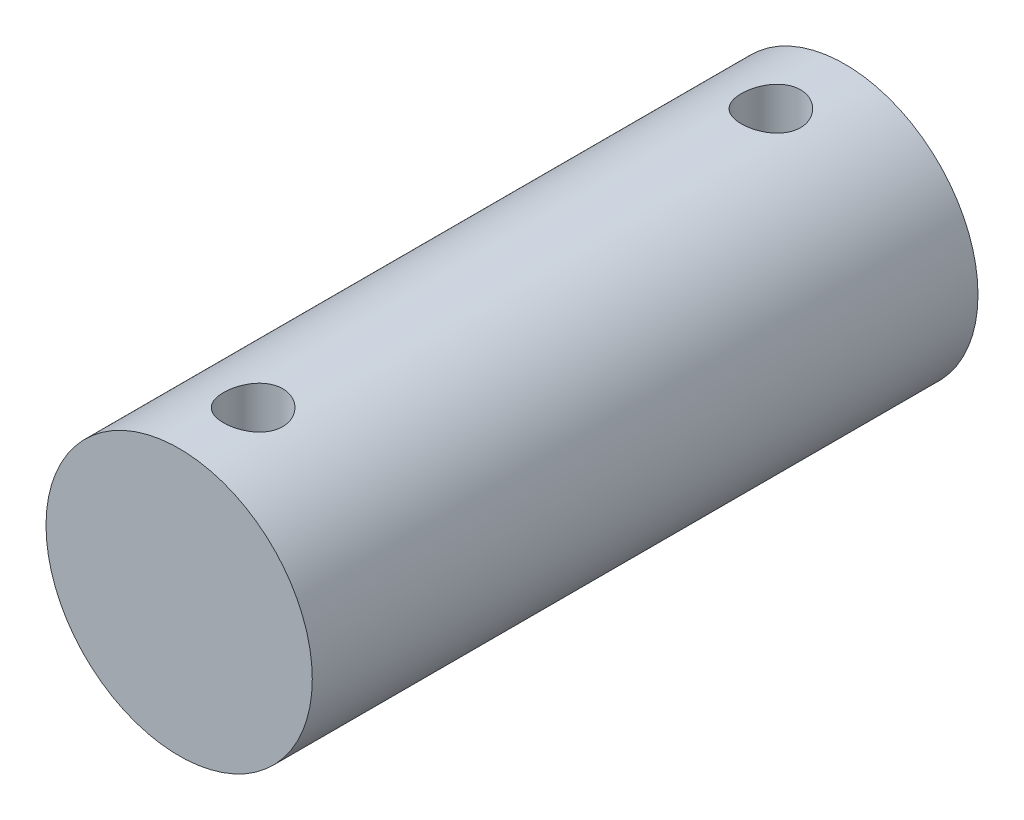
SolidWorks part; units mm, degrees
ref_plane "Front Plane" through (0, 0, 0) normal (0, 0, 1) x (1, 0, 0)
ref_plane "Top Plane" through (0, 0, 0) normal (0, 1, 0) x (1, 0, 0)
ref_plane "Right Plane" through (0, 0, 0) normal (1, 0, 0) x (0, 0, -1)
sketch "Sketch1" plane through (0, 0, 0) normal (0, 0, 1) x (1, 0, 0)
  circle A0 centre (0, 0) radius 9
  dimension "D1" = 18
extrude "Boss-Extrude1" add sketch "Sketch1" along normal blind 12.5
sketch "Sketch2" plane through (0, 0, 12.5) normal (0, 0, 1) x (1, 0, 0)
  circle A1 centre (0, 0) radius 9
  dimension "D1" = 18
extrude "Boss-Extrude2" add sketch "Sketch2" along normal blind 10
sketch "Sketch3" plane through (0, 0, 0) normal (0, 1, 0) x (1, 0, 0)
  line L0 (-9, -22.5) -> (9, -22.5) construction
  circle A0 centre (0, -17.5) radius 2
  dimension "D1" = 4
  dimension "D2" = 5
extrude "Cut-Extrude1" cut sketch "Sketch3" against normal through all and the other way through all
mirror "Mirror1" about plane through (0, 0, 0) normal (0, 0, 1) of bodies 105
